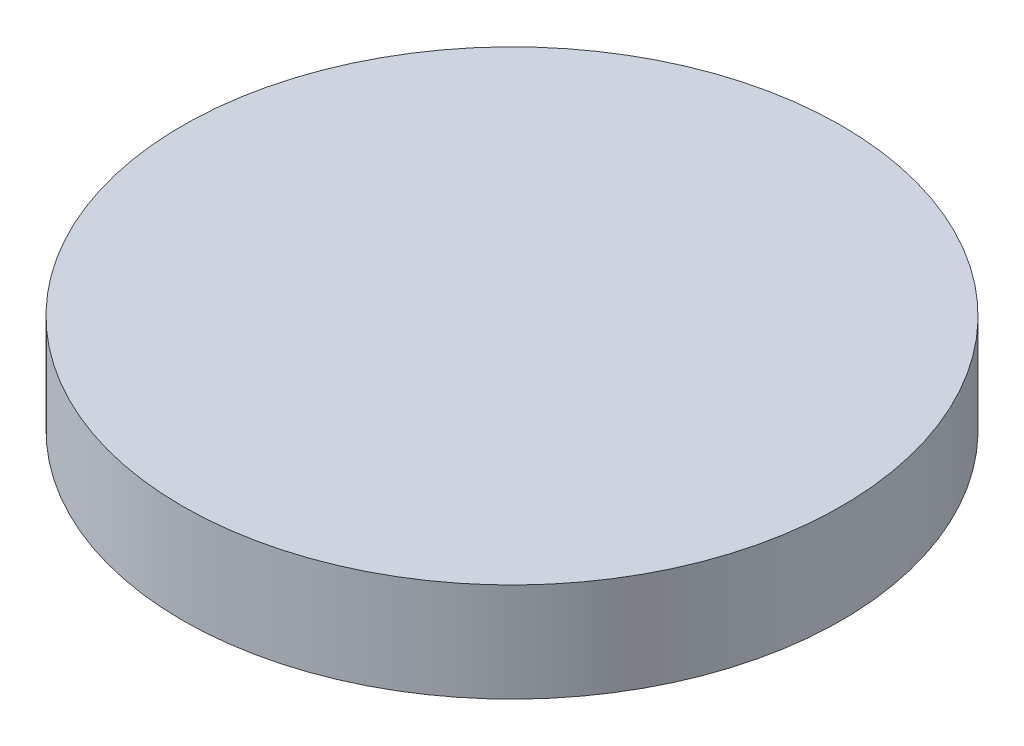
SolidWorks part; units mm, degrees
material "Custom Plastic"
ref_plane "Front Plane" through (0, 0, 0) normal (0, 0, 1) x (1, 0, 0)
ref_plane "Top Plane" through (0, 0, 0) normal (0, 1, 0) x (1, 0, 0)
ref_plane "Right Plane" through (0, 0, 0) normal (1, 0, 0) x (0, 0, -1)
sketch "Sketch1" plane through (0, 0, 0) normal (0, 1, 0) x (1, 0, 0)
  circle A0 centre (0, 0) radius 50
  dimension "D1" = 100
extrude "Boss-Extrude1" add sketch "Sketch1" along normal blind 15
